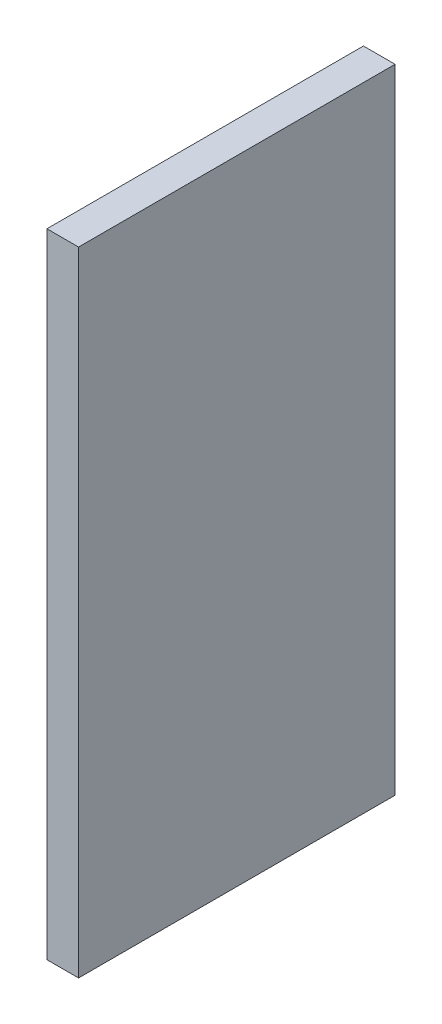
SolidWorks part; units mm, degrees
ref_plane "Front Plane" through (0, 0, 0) normal (0, 0, 1) x (1, 0, 0)
ref_plane "Top Plane" through (0, 0, 0) normal (0, 1, 0) x (1, 0, 0)
ref_plane "Right Plane" through (0, 0, 0) normal (1, 0, 0) x (0, 0, -1)
sketch "Sketch1" plane through (0, 0, 0) normal (1, 0, 0) x (0, 0, -1)
  line L1 (-20, -42.5) -> (20, -42.5)
  line L2 (-20, -42.5) -> (-20, -122.5)
  line L3 (-20, -122.5) -> (20, -122.5)
  line L4 (20, -42.5) -> (20, -122.5)
  point P0 (0, 0)
  dimension "D3" = 80
  dimension "D2" = 40
extrude "Boss-Extrude1" add sketch "Sketch1" along normal blind 4
